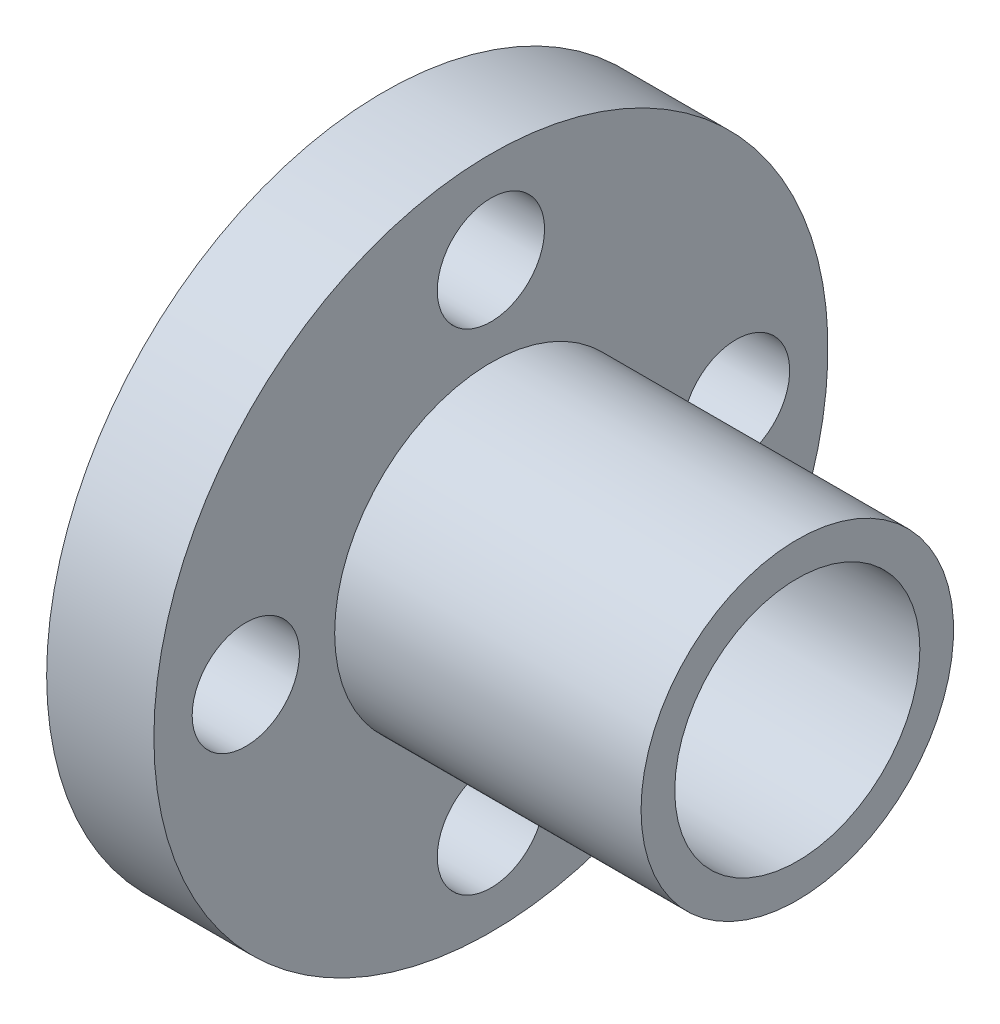
SolidWorks part; units mm, degrees
ref_plane "前视基准面" through (0, 0, 0) normal (0, 0, 1) x (1, 0, 0)
ref_plane "上视基准面" through (0, 0, 0) normal (0, 1, 0) x (1, 0, 0)
ref_plane "右视基准面" through (0, 0, 0) normal (1, 0, 0) x (0, 0, -1)
other "Configuration Table"
sketch "草图1" plane through (0, 0, 0) normal (0, 0, 1) x (1, 0, 0)
  line L0 (0, 0) -> (0, 20.3509) construction
  line L1 (0, 0) -> (34.2374, 0) construction
  line L2 (-9.3535, 5.1) -> (-7.8535, 5.1)
  line L3 (-7.8535, 5.1) -> (-7.8535, 11)
  line L4 (-7.8535, 11) -> (-4.3535, 11)
  line L5 (-4.3535, 11) -> (-4.3535, 9.75)
  line L6 (5.6465, 5.1) -> (5.6465, 4)
  line L7 (-9.3535, 5.1) -> (-9.3535, 4)
  line L8 (-4.3535, 5.1) -> (5.6465, 5.1)
  line L11 (-4.3535, 8) -> (-4.3535, 9.75)
  line L13 (-4.3535, 8) -> (-4.3535, 5.1)
  line L14 (-9.3535, 4) -> (5.6465, 4)
  dimension "D1" = 3.5
  dimension "D2" = 15
  dimension "D3" = 1.5
  dimension "D4" = 10
  dimension "D5" = 11
  dimension "D6" = 5.1
  dimension "D10" = 4
revolve "旋转1" add sketch "草图1" angle 360 about L1
sketch "草图4" plane through (-7.8535, 0, 0) normal (-1, 0, 0) x (0, 0, 1)
  line L0 (0.0642, 0) -> (10.741, 0) construction
  circle A0 centre (8, 0) radius 1.75
  circle A1 centre (0, -8) radius 1.75
  circle A2 centre (-8, 0) radius 1.75
  circle A3 centre (0, 8) radius 1.75
  point P15 (0, 0)
  dimension "D1" = 3.5
  dimension "D2" = 8
  dimension "D3" = 4
extrude "切除-拉伸1" cut sketch "草图4" against normal through all contours A3 | A0 | A1 | A2
